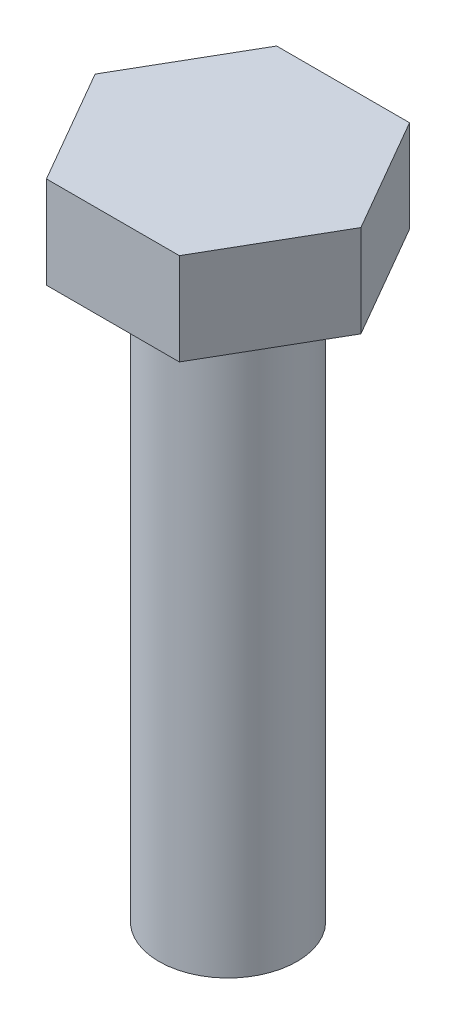
SolidWorks part; units mm, degrees
ref_plane "前视基准面" through (0, 0, 0) normal (0, 0, 1) x (1, 0, 0)
ref_plane "上视基准面" through (0, 0, 0) normal (0, 1, 0) x (1, 0, 0)
ref_plane "右视基准面" through (0, 0, 0) normal (1, 0, 0) x (0, 0, -1)
other "Configuration Table"
sketch "Shank Profile" plane through (0, 0, 0) normal (0, 1, 0) x (1, 0, 0)
  circle A0 centre (0, 0) radius 3
  point P2 (0, 0)
  dimension "D1" = 6
extrude "Shank" add sketch "Shank Profile" along normal blind 25
sketch "Head Profile" plane through (0, 0, 0) normal (0, 1, 0) x (1, 0, 0)
  line L0 (5.7735, 0) -> (2.8868, -5)
  line L1 (2.8868, -5) -> (-2.8868, -5)
  line L2 (-2.8868, -5) -> (-5.7735, 0)
  line L3 (-5.7735, 0) -> (-2.8868, 5)
  line L4 (-2.8868, 5) -> (2.8868, 5)
  line L5 (2.8868, 5) -> (5.7735, 0)
  point P6 (0, 0)
  dimension "D1" = 2.8868
  dimension "D2" = 5.7735
  dimension "D3" = 8.6603
  dimension "D4" = 11.547
  dimension "D5" = 5
  dimension "D6" = 10
extrude "Head" add sketch "Head Profile" along normal blind 4 from offset 25
